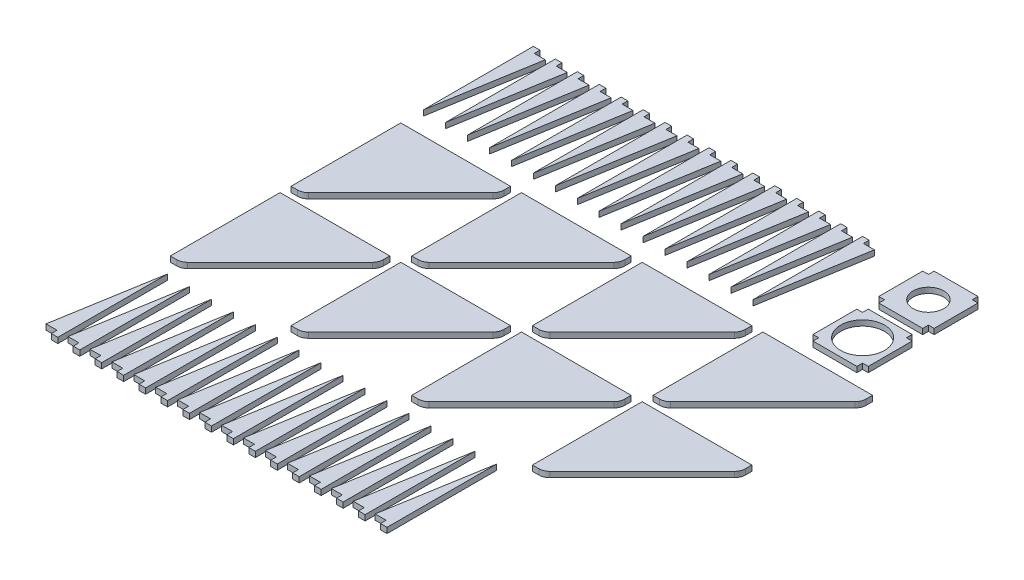
SolidWorks part; units mm, degrees
ref_plane "Front Plane" through (0, 0, 0) normal (0, 0, 1) x (1, 0, 0)
ref_plane "Top Plane" through (0, 0, 0) normal (0, 1, 0) x (1, 0, 0)
ref_plane "Right Plane" through (0, 0, 0) normal (1, 0, 0) x (0, 0, -1)
sketch "Sketch2" plane through (0, 0, 0) normal (0, 1, 0) x (1, 0, 0)
  line L6 (-209.1635, -277.3688) -> (95.6365, -277.3688)
  line L7 (-209.1635, -277.3688) -> (-209.1635, 27.4312)
  line L8 (95.6365, -277.3688) -> (95.6365, 27.4312)
  line L9 (-209.1635, 27.4312) -> (95.6365, 27.4312)
  dimension "D5" = 304.8
  dimension "D6" = 304.8
extrude "Boss-Extrude1" add sketch "Sketch2" along normal blind 3.175
sketch "Sketch3" plane through (0, 3.175, 0) normal (0, 1, 0) x (1, 0, 0)
  line L0 (-196.4635, 14.7312) -> (-196.4635, -48.7688)
  line L1 (-196.4635, -48.7688) -> (-186.3035, 11.4292)
  line L2 (-186.3035, 11.4292) -> (-192.6535, 11.4292)
  line L3 (-192.6535, 11.4292) -> (-192.6535, 14.7312)
  line L4 (-192.6535, 14.7312) -> (-196.4635, 14.7312)
  line L5 (-209.1635, 27.4312) -> (-209.1635, -277.3688) construction
  line L6 (95.6365, 27.4312) -> (-209.1635, 27.4312) construction
  line L7 (-179.9535, 14.7312) -> (-183.7635, 14.7312)
  line L8 (-183.7635, 14.7312) -> (-183.7635, -48.7688)
  line L9 (-183.7635, -48.7688) -> (-173.6035, 11.4292)
  line L10 (-173.6035, 11.4292) -> (-179.9535, 11.4292)
  line L11 (-179.9535, 11.4292) -> (-179.9535, 14.7312)
  line L12 (-167.2535, 14.7312) -> (-171.0635, 14.7312)
  line L13 (-171.0635, 14.7312) -> (-171.0635, -48.7688)
  line L14 (-171.0635, -48.7688) -> (-160.9035, 11.4292)
  line L15 (-160.9035, 11.4292) -> (-167.2535, 11.4292)
  line L16 (-167.2535, 11.4292) -> (-167.2535, 14.7312)
  line L17 (-154.5535, 14.7312) -> (-158.3635, 14.7312)
  line L18 (-158.3635, 14.7312) -> (-158.3635, -48.7688)
  line L19 (-158.3635, -48.7688) -> (-148.2035, 11.4292)
  line L20 (-148.2035, 11.4292) -> (-154.5535, 11.4292)
  line L21 (-154.5535, 11.4292) -> (-154.5535, 14.7312)
  line L22 (-141.8535, 14.7312) -> (-145.6635, 14.7312)
  line L23 (-145.6635, 14.7312) -> (-145.6635, -48.7688)
  line L24 (-145.6635, -48.7688) -> (-135.5035, 11.4292)
  line L25 (-135.5035, 11.4292) -> (-141.8535, 11.4292)
  line L26 (-141.8535, 11.4292) -> (-141.8535, 14.7312)
  line L27 (-129.1535, 14.7312) -> (-132.9635, 14.7312)
  line L28 (-132.9635, 14.7312) -> (-132.9635, -48.7688)
  line L29 (-132.9635, -48.7688) -> (-122.8035, 11.4292)
  line L30 (-122.8035, 11.4292) -> (-129.1535, 11.4292)
  line L31 (-129.1535, 11.4292) -> (-129.1535, 14.7312)
  line L32 (-116.4535, 14.7312) -> (-120.2635, 14.7312)
  line L33 (-120.2635, 14.7312) -> (-120.2635, -48.7688)
  line L34 (-120.2635, -48.7688) -> (-110.1035, 11.4292)
  line L35 (-110.1035, 11.4292) -> (-116.4535, 11.4292)
  line L36 (-116.4535, 11.4292) -> (-116.4535, 14.7312)
  line L37 (-103.7535, 14.7312) -> (-107.5635, 14.7312)
  line L38 (-107.5635, 14.7312) -> (-107.5635, -48.7688)
  line L39 (-107.5635, -48.7688) -> (-97.4035, 11.4292)
  line L40 (-97.4035, 11.4292) -> (-103.7535, 11.4292)
  line L41 (-103.7535, 11.4292) -> (-103.7535, 14.7312)
  line L42 (-91.0535, 14.7312) -> (-94.8635, 14.7312)
  line L43 (-94.8635, 14.7312) -> (-94.8635, -48.7688)
  line L44 (-94.8635, -48.7688) -> (-84.7035, 11.4292)
  line L45 (-84.7035, 11.4292) -> (-91.0535, 11.4292)
  line L46 (-91.0535, 11.4292) -> (-91.0535, 14.7312)
  line L47 (-78.3535, 14.7312) -> (-82.1635, 14.7312)
  line L48 (-82.1635, 14.7312) -> (-82.1635, -48.7688)
  line L49 (-82.1635, -48.7688) -> (-72.0035, 11.4292)
  line L50 (-72.0035, 11.4292) -> (-78.3535, 11.4292)
  line L51 (-78.3535, 11.4292) -> (-78.3535, 14.7312)
  line L52 (-65.6535, 14.7312) -> (-69.4635, 14.7312)
  line L53 (-69.4635, 14.7312) -> (-69.4635, -48.7688)
  line L54 (-69.4635, -48.7688) -> (-59.3035, 11.4292)
  line L55 (-59.3035, 11.4292) -> (-65.6535, 11.4292)
  line L56 (-65.6535, 11.4292) -> (-65.6535, 14.7312)
  line L57 (-52.9535, 14.7312) -> (-56.7635, 14.7312)
  line L58 (-56.7635, 14.7312) -> (-56.7635, -48.7688)
  line L59 (-56.7635, -48.7688) -> (-46.6035, 11.4292)
  line L60 (-46.6035, 11.4292) -> (-52.9535, 11.4292)
  line L61 (-52.9535, 11.4292) -> (-52.9535, 14.7312)
  line L62 (-40.2535, 14.7312) -> (-44.0635, 14.7312)
  line L63 (-44.0635, 14.7312) -> (-44.0635, -48.7688)
  line L64 (-44.0635, -48.7688) -> (-33.9035, 11.4292)
  line L65 (-33.9035, 11.4292) -> (-40.2535, 11.4292)
  line L66 (-40.2535, 11.4292) -> (-40.2535, 14.7312)
  line L67 (-27.5535, 14.7312) -> (-31.3635, 14.7312)
  line L68 (-31.3635, 14.7312) -> (-31.3635, -48.7688)
  line L69 (-31.3635, -48.7688) -> (-21.2035, 11.4292)
  line L70 (-21.2035, 11.4292) -> (-27.5535, 11.4292)
  line L71 (-27.5535, 11.4292) -> (-27.5535, 14.7312)
  line L72 (-14.8535, 14.7312) -> (-18.6635, 14.7312)
  line L73 (-18.6635, 14.7312) -> (-18.6635, -48.7688)
  line L74 (-18.6635, -48.7688) -> (-8.5035, 11.4292)
  line L75 (-8.5035, 11.4292) -> (-14.8535, 11.4292)
  line L76 (-14.8535, 11.4292) -> (-14.8535, 14.7312)
  line L77 (-2.1535, 14.7312) -> (-5.9635, 14.7312)
  line L78 (-5.9635, 14.7312) -> (-5.9635, -48.7688)
  line L79 (-5.9635, -48.7688) -> (4.1965, 11.4292)
  line L80 (4.1965, 11.4292) -> (-2.1535, 11.4292)
  line L81 (-2.1535, 11.4292) -> (-2.1535, 14.7312)
  line L326 (-133.5339, -68.3803) -> (-132.9635, -68.3803)
  line L328 (32.1365, 14.7312) -> (28.8345, 14.7312)
  line L329 (32.1365, -10.6688) -> (28.8345, -10.6688)
  line L330 (28.8345, 14.7312) -> (28.8345, -10.6688)
  line L331 (-196.4635, -62.0303) -> (-132.9635, -62.0303)
  line L333 (32.1365, 14.7312) -> (32.1365, 18.0332)
  line L334 (57.5365, 14.7312) -> (57.5365, 18.0332)
  line L335 (32.1365, 18.0332) -> (57.5365, 18.0332)
  line L336 (32.1365, -10.6688) -> (32.1365, -13.9708)
  line L337 (57.5365, -13.9708) -> (32.1365, -13.9708)
  line L338 (57.5365, -10.6688) -> (57.5365, -13.9708)
  line L339 (-196.4635, -62.0303) -> (-196.4635, -125.5303)
  line L340 (57.5365, 14.7312) -> (60.8385, 14.7312)
  line L341 (60.8385, -10.6688) -> (60.8385, 14.7312)
  line L342 (57.5365, -10.6688) -> (60.8385, -10.6688)
  line L343 (-196.4635, -125.5303) -> (-192.7438, -125.5303)
  line L352 (57.5365, -52.0708) -> (32.1365, -52.0708)
  line L353 (57.5365, -52.0708) -> (57.5365, -48.7688)
  line L354 (32.1365, -20.0668) -> (57.5365, -20.0668)
  line L355 (60.8385, -48.7688) -> (60.8385, -23.3688)
  line L356 (57.5365, -48.7688) -> (60.8385, -48.7688)
  line L357 (-132.9635, -62.0303) -> (-132.9635, -65.7501)
  line L359 (32.1365, -23.3688) -> (32.1365, -20.0668)
  line L361 (-190.1135, -124.96) -> (-190.1135, -125.5303)
  line L362 (32.1365, -48.7688) -> (28.8345, -48.7688)
  line L363 (32.1365, -48.7688) -> (32.1365, -52.0708)
  line L364 (-190.1135, -68.3803) -> (-139.3135, -68.3803) construction
  line L365 (-10.4536, -205.1954) -> (-20.6136, -265.3934)
  line L366 (-190.1135, -68.3803) -> (-190.1135, -119.1803) construction
  line L367 (-134.8234, -70.2402) -> (-188.2536, -123.6705)
  line L368 (-196.4635, -125.5303) -> (-132.9635, -125.5303) construction
  line L369 (-132.9635, -62.0303) -> (-132.9635, -125.5303) construction
  line L370 (-126.6135, -125.5303) -> (-122.8938, -125.5303)
  line L371 (57.5365, -23.3688) -> (60.8385, -23.3688)
  line L372 (-126.6135, -62.0303) -> (-126.6135, -125.5303)
  line L373 (-126.6135, -62.0303) -> (-63.1135, -62.0303)
  line L374 (32.1365, -23.3688) -> (28.8345, -23.3688)
  line L375 (57.5365, -23.3688) -> (57.5365, -20.0668)
  line L376 (-63.1135, -62.0303) -> (-63.1135, -65.7501)
  line L377 (28.8345, -23.3688) -> (28.8345, -48.7688)
  line L378 (-139.3135, -68.3803) -> (-139.3135, -119.1803) construction
  line L379 (-190.1135, -119.1803) -> (-139.3135, -119.1803) construction
  line L380 (-64.9734, -70.2402) -> (-118.4036, -123.6705)
  line L381 (-56.7635, -125.5303) -> (-53.0438, -125.5303)
  line L382 (-56.7635, -62.0303) -> (-56.7635, -125.5303)
  line L383 (-56.7635, -62.0303) -> (6.7365, -62.0303)
  line L384 (6.7365, -62.0303) -> (6.7365, -65.7501)
  line L385 (4.8766, -70.2402) -> (-48.5536, -123.6705)
  line L386 (13.0865, -125.5303) -> (16.8062, -125.5303)
  line L387 (13.0865, -62.0303) -> (13.0865, -125.5303)
  line L388 (13.0865, -62.0303) -> (76.5865, -62.0303)
  line L389 (76.5865, -62.0303) -> (76.5865, -65.7501)
  line L390 (74.7266, -70.2402) -> (21.2964, -123.6705)
  line L391 (76.5865, -131.8803) -> (76.5865, -135.6001)
  line L392 (-134.8234, -140.0902) -> (-188.2536, -193.5205)
  line L393 (-126.6135, -131.8803) -> (-63.1135, -131.8803)
  line L394 (-56.7635, -195.3803) -> (-53.0438, -195.3803)
  line L395 (-126.6135, -195.3803) -> (-122.8938, -195.3803)
  line L396 (-126.6135, -131.8803) -> (-126.6135, -195.3803)
  line L397 (-56.7635, -131.8803) -> (-56.7635, -195.3803)
  line L398 (13.0865, -195.3803) -> (16.8062, -195.3803)
  line L399 (-63.1135, -131.8803) -> (-63.1135, -135.6001)
  line L400 (4.8766, -140.0902) -> (-48.5536, -193.5205)
  line L401 (74.7266, -140.0902) -> (21.2964, -193.5205)
  line L402 (-132.9635, -131.8803) -> (-132.9635, -135.6001)
  line L403 (6.7365, -131.8803) -> (6.7365, -135.6001)
  line L404 (-196.4635, -131.8803) -> (-196.4635, -195.3803)
  line L405 (-196.4635, -195.3803) -> (-192.7438, -195.3803)
  line L406 (-64.9734, -140.0902) -> (-118.4036, -193.5205)
  line L407 (-56.7635, -131.8803) -> (6.7365, -131.8803)
  line L408 (13.0865, -131.8803) -> (13.0865, -195.3803)
  line L409 (-196.4635, -131.8803) -> (-132.9635, -131.8803)
  line L410 (13.0865, -131.8803) -> (76.5865, -131.8803)
  line L411 (-90.4636, -265.3934) -> (-90.4636, -268.6954)
  line L412 (-192.0636, -268.6954) -> (-188.2536, -268.6954)
  line L413 (-52.3636, -265.3934) -> (-52.3636, -268.6954)
  line L414 (-73.9536, -205.1954) -> (-84.1136, -265.3934)
  line L415 (-103.1636, -268.6954) -> (-99.3536, -268.6954)
  line L416 (-153.9636, -268.6954) -> (-150.1536, -268.6954)
  line L417 (-48.5536, -205.1954) -> (-58.7136, -265.3934)
  line L418 (-86.6536, -268.6954) -> (-86.6536, -205.1954)
  line L419 (-99.3536, -205.1954) -> (-109.5136, -265.3934)
  line L420 (-134.9136, -265.3934) -> (-128.5636, -265.3934)
  line L421 (-166.6636, -268.6954) -> (-162.8536, -268.6954)
  line L422 (-175.5536, -205.1954) -> (-185.7136, -265.3934)
  line L423 (-1.5636, -265.3934) -> (-1.5636, -268.6954)
  line L424 (-35.8536, -268.6954) -> (-35.8536, -205.1954)
  line L425 (-73.9536, -268.6954) -> (-73.9536, -205.1954)
  line L426 (-99.3536, -268.6954) -> (-99.3536, -205.1954)
  line L427 (-162.8536, -205.1954) -> (-173.0136, -265.3934)
  line L428 (-14.2636, -268.6954) -> (-10.4536, -268.6954)
  line L429 (-23.1536, -268.6954) -> (-23.1536, -205.1954)
  line L430 (-112.0536, -205.1954) -> (-122.2136, -265.3934)
  line L431 (-150.1536, -205.1954) -> (-160.3136, -265.3934)
  line L432 (-160.3136, -265.3934) -> (-153.9636, -265.3934)
  line L433 (-175.5536, -268.6954) -> (-175.5536, -205.1954)
  line L434 (-20.6136, -265.3934) -> (-14.2636, -265.3934)
  line L435 (-58.7136, -265.3934) -> (-52.3636, -265.3934)
  line L436 (-122.2136, -265.3934) -> (-115.8636, -265.3934)
  line L437 (-162.8536, -268.6954) -> (-162.8536, -205.1954)
  line L438 (-166.6636, -265.3934) -> (-166.6636, -268.6954)
  line L439 (2.2464, -268.6954) -> (2.2464, -205.1954)
  line L440 (-77.7636, -265.3934) -> (-77.7636, -268.6954)
  line L441 (-109.5136, -265.3934) -> (-103.1636, -265.3934)
  line L442 (-137.4536, -205.1954) -> (-147.6136, -265.3934)
  line L443 (2.2464, -205.1954) -> (-7.9136, -265.3934)
  line L444 (-61.2536, -205.1954) -> (-71.4136, -265.3934)
  line L445 (-179.3636, -268.6954) -> (-175.5536, -268.6954)
  line L446 (-1.5636, -268.6954) -> (2.2464, -268.6954)
  line L447 (-26.9636, -268.6954) -> (-23.1536, -268.6954)
  line L448 (-35.8536, -205.1954) -> (-46.0136, -265.3934)
  line L449 (-115.8636, -265.3934) -> (-115.8636, -268.6954)
  line L450 (-150.1536, -268.6954) -> (-150.1536, -205.1954)
  line L451 (-10.4536, -268.6954) -> (-10.4536, -205.1954)
  line L452 (-26.9636, -265.3934) -> (-26.9636, -268.6954)
  line L453 (-90.4636, -268.6954) -> (-86.6536, -268.6954)
  line L454 (-185.7136, -265.3934) -> (-179.3636, -265.3934)
  line L455 (-179.3636, -265.3934) -> (-179.3636, -268.6954)
  line L456 (-188.2536, -205.1954) -> (-198.4136, -265.3934)
  line L457 (-14.2636, -265.3934) -> (-14.2636, -268.6954)
  line L458 (-33.3136, -265.3934) -> (-26.9636, -265.3934)
  line L459 (-137.4536, -268.6954) -> (-137.4536, -205.1954)
  line L460 (-153.9636, -265.3934) -> (-153.9636, -268.6954)
  line L461 (-52.3636, -268.6954) -> (-48.5536, -268.6954)
  line L462 (-48.5536, -268.6954) -> (-48.5536, -205.1954)
  line L463 (-84.1136, -265.3934) -> (-77.7636, -265.3934)
  line L464 (-103.1636, -265.3934) -> (-103.1636, -268.6954)
  line L465 (-147.6136, -265.3934) -> (-141.2636, -265.3934)
  line L466 (-86.6536, -205.1954) -> (-96.8136, -265.3934)
  line L467 (-115.8636, -268.6954) -> (-112.0536, -268.6954)
  line L468 (-124.7536, -268.6954) -> (-124.7536, -205.1954)
  line L469 (-198.4136, -265.3934) -> (-192.0636, -265.3934)
  line L470 (-46.0136, -265.3934) -> (-39.6636, -265.3934)
  line L471 (-65.0636, -265.3934) -> (-65.0636, -268.6954)
  line L472 (-77.7636, -268.6954) -> (-73.9536, -268.6954)
  line L473 (-96.8136, -265.3934) -> (-90.4636, -265.3934)
  line L474 (-141.2636, -268.6954) -> (-137.4536, -268.6954)
  line L475 (-173.0136, -265.3934) -> (-166.6636, -265.3934)
  line L476 (-39.6636, -265.3934) -> (-39.6636, -268.6954)
  line L477 (-61.2536, -268.6954) -> (-61.2536, -205.1954)
  line L478 (-71.4136, -265.3934) -> (-65.0636, -265.3934)
  line L479 (-112.0536, -268.6954) -> (-112.0536, -205.1954)
  line L480 (-128.5636, -265.3934) -> (-128.5636, -268.6954)
  line L481 (-188.2536, -268.6954) -> (-188.2536, -205.1954)
  line L482 (-192.0636, -265.3934) -> (-192.0636, -268.6954)
  line L483 (-7.9136, -265.3934) -> (-1.5636, -265.3934)
  line L484 (-39.6636, -268.6954) -> (-35.8536, -268.6954)
  line L485 (-65.0636, -268.6954) -> (-61.2536, -268.6954)
  line L486 (-23.1536, -205.1954) -> (-33.3136, -265.3934)
  line L487 (-128.5636, -268.6954) -> (-124.7536, -268.6954)
  line L488 (-124.7536, -205.1954) -> (-134.9136, -265.3934)
  line L489 (-141.2636, -265.3934) -> (-141.2636, -268.6954)
  circle A0 centre (44.8365, 2.0312) radius 8.89
  circle A1 centre (44.8365, -36.0688) radius 12.7
  arc A2 (-132.9635, -65.7501) -> (-134.8234, -70.2402) centre (-139.3135, -65.7501) cw
  arc A3 (-192.7438, -125.5303) -> (-188.2536, -123.6705) centre (-192.7438, -119.1803) ccw
  arc A4 (-122.8938, -125.5303) -> (-118.4036, -123.6705) centre (-122.8938, -119.1803) ccw
  arc A5 (-63.1135, -65.7501) -> (-64.9734, -70.2402) centre (-69.4635, -65.7501) cw
  arc A6 (-53.0438, -125.5303) -> (-48.5536, -123.6705) centre (-53.0438, -119.1803) ccw
  arc A7 (6.7365, -65.7501) -> (4.8766, -70.2402) centre (0.3865, -65.7501) cw
  arc A8 (16.8062, -125.5303) -> (21.2964, -123.6705) centre (16.8062, -119.1803) ccw
  arc A9 (76.5865, -65.7501) -> (74.7266, -70.2402) centre (70.2365, -65.7501) cw
  arc A10 (6.7365, -135.6001) -> (4.8766, -140.0902) centre (0.3865, -135.6001) cw
  arc A11 (-63.1135, -135.6001) -> (-64.9734, -140.0902) centre (-69.4635, -135.6001) cw
  arc A12 (-122.8938, -195.3803) -> (-118.4036, -193.5205) centre (-122.8938, -189.0303) ccw
  arc A13 (16.8062, -195.3803) -> (21.2964, -193.5205) centre (16.8062, -189.0303) ccw
  arc A14 (76.5865, -135.6001) -> (74.7266, -140.0902) centre (70.2365, -135.6001) cw
  arc A15 (-132.9635, -135.6001) -> (-134.8234, -140.0902) centre (-139.3135, -135.6001) cw
  arc A16 (-53.0438, -195.3803) -> (-48.5536, -193.5205) centre (-53.0438, -189.0303) ccw
  arc A17 (-192.7438, -195.3803) -> (-188.2536, -193.5205) centre (-192.7438, -189.0303) ccw
  dimension "D24" = 17.78
  dimension "D25" = 25.4
  dimension "D14" = 6.35
  dimension "D15" = 6.35
  dimension "D1" = 63.5
  dimension "D2" = 3.302
  dimension "D3" = 6.35
  dimension "D4" = 3.81
  dimension "D5" = 12.7
  dimension "D6" = 12.7
  dimension "D11" = 63.5
  dimension "D12" = 63.5
  dimension "D13" = 6.35
  dimension "D16" = 4
  dimension "D17" = 25.4
  dimension "D21" = 3.302
  dimension "D22" = 3.302
  dimension "D23" = 3.302
  dimension "D7" = 16
extrude "Cut-Extrude1" cut sketch "Sketch3" against normal through all both and the other way through all
